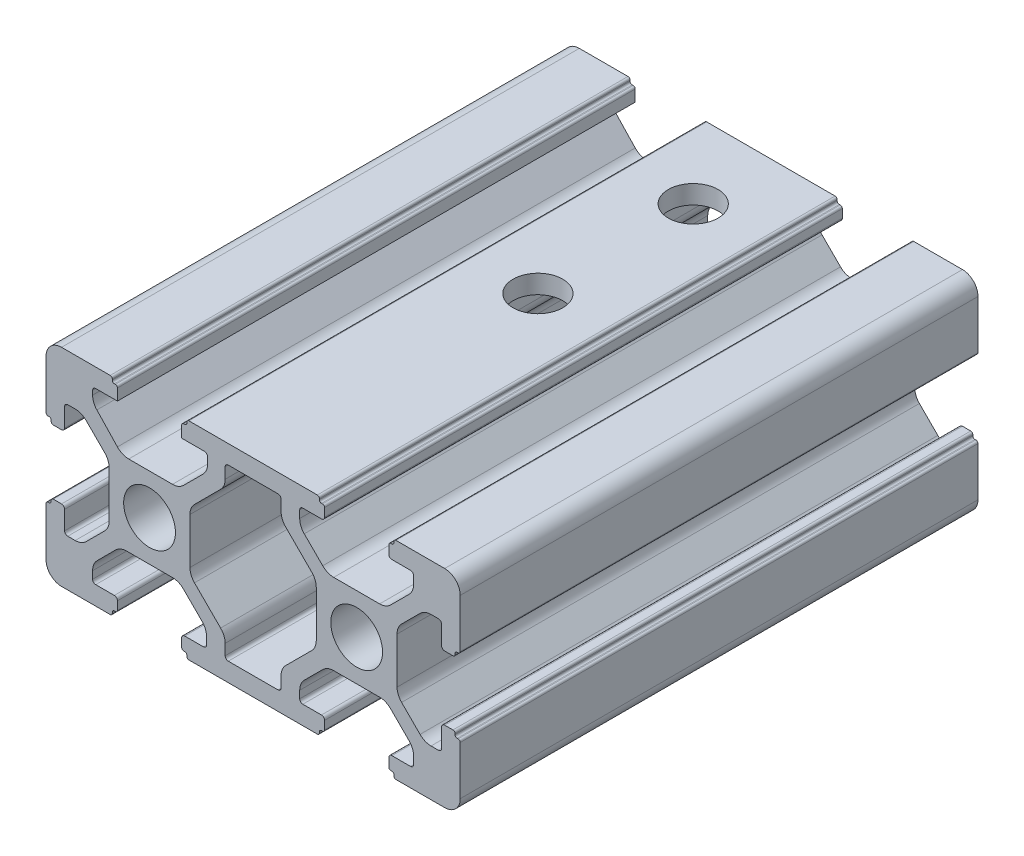
SolidWorks part; units mm, degrees
material "6063-O"
ref_plane "Front Plane" through (0, 0, 0) normal (0, 0, 1) x (1, 0, 0)
ref_plane "Top Plane" through (0, 0, 0) normal (0, 1, 0) x (1, 0, 0)
ref_plane "Right Plane" through (0, 0, 0) normal (1, 0, 0) x (0, 0, -1)
sketch "Sketch1" plane through (0, 0, 0) normal (0, 0, 1) x (1, 0, 0)
  line L0 (1.5, 0) -> (6.2, 0)
  line L1 (40, 1.5) -> (40, 6.2)
  line L2 (38.5, 20) -> (33.8, 20)
  line L3 (0, 18.5) -> (0, 13.8)
  line L4 (17.6, 1.8) -> (22.4, 1.8)
  line L5 (32.218, 13.9) -> (27.782, 13.9)
  line L6 (26.1, 12.218) -> (26.1, 7.782)
  line L7 (17.6, 18.2) -> (22.4, 18.2)
  line L8 (12.218, 13.9) -> (7.9864, 13.9)
  line L9 (6.1, 12.218) -> (6.1, 7.782)
  line L10 (7.782, 6.1) -> (12.218, 6.1)
  line L11 (13.9, 7.782) -> (13.9, 12.218)
  line L12 (27.782, 6.1) -> (32.218, 6.1)
  line L13 (33.9, 7.782) -> (33.9, 12.218)
  line L14 (26.7213, 14.3393) -> (24.9393, 16.1213)
  line L15 (33.2787, 14.3393) -> (35.0607, 16.1213)
  line L16 (34.3393, 13.2787) -> (36.1213, 15.0607)
  line L17 (25.6607, 6.7213) -> (23.1393, 4.2)
  line L18 (15.2, 1.8) -> (13.4, 1.8)
  line L19 (26.7213, 5.6607) -> (24.9393, 3.8787)
  line L20 (24.8, 1.8) -> (26.6, 1.8)
  line L21 (15.3, 18.2) -> (13.1, 18.2)
  line L22 (13.2787, 14.3393) -> (15.1607, 16.2213)
  line L23 (14.3393, 13.2787) -> (16.8607, 15.8)
  line L24 (5.6607, 6.7213) -> (3.8787, 4.9393)
  line L25 (6.7213, 5.6607) -> (4.9393, 3.8787)
  line L26 (6.897, 14.3689) -> (4.9106, 16.4674)
  line L27 (5.6607, 13.2787) -> (3.8787, 15.0607)
  line L28 (14.3393, 6.7213) -> (16.8607, 4.2)
  line L29 (13.2787, 5.6607) -> (15.0607, 3.8787)
  line L30 (24.8, 18.2) -> (26.6, 18.2)
  line L31 (25.6607, 13.2787) -> (23.1393, 15.8)
  line L32 (34.3393, 6.7213) -> (36.1213, 4.9393)
  line L33 (33.2787, 5.6607) -> (35.0607, 3.8787)
  line L34 (1.8, 15.2) -> (1.8, 13.4)
  line L35 (24.5, 2.1) -> (24.5, 2.818)
  line L36 (4.5, 2.1) -> (4.5, 2.818)
  line L37 (2.818, 4.5) -> (2.1, 4.5)
  line L38 (4.5, 17.9) -> (4.5, 17.4986)
  line L39 (2.818, 15.5) -> (2.1, 15.5)
  line L40 (15.6, 17.9) -> (15.6, 17.282)
  line L41 (15.5, 2.818) -> (15.5, 2.1)
  line L42 (38.2, 15.2) -> (38.2, 13.4)
  line L43 (35.5, 2.818) -> (35.5, 2.1)
  line L44 (37.182, 4.5) -> (37.9, 4.5)
  line L45 (35.5, 17.182) -> (35.5, 17.9)
  line L46 (37.182, 15.5) -> (37.9, 15.5)
  line L47 (17.3, 2.1) -> (17.3, 3.1393)
  line L48 (22.7, 2.1) -> (22.7, 3.1393)
  line L49 (17.3, 17.9) -> (17.3, 16.8607)
  line L50 (22.7, 17.9) -> (22.7, 16.8607)
  line L51 (24.5, 17.9) -> (24.5, 17.182)
  line L52 (6.9, 19.3) -> (6.9, 18.2)
  line L53 (13.1, 19.3) -> (13.1, 18.2)
  line L54 (6.9, 1.5) -> (6.9, 0.7)
  line L55 (13.1, 1.5) -> (13.1, 0.7)
  line L56 (13.8, 0) -> (26.2, 0)
  line L57 (6.6, 1.8) -> (4.8, 1.8)
  line L58 (6.9, 18.2) -> (4.8, 18.2)
  line L59 (6.2, 20) -> (1.5, 20)
  line L60 (39.3, 6.9) -> (38.5, 6.9)
  line L61 (39.3, 13.1) -> (38.5, 13.1)
  line L62 (1.5, 13.1) -> (0.7, 13.1)
  line L63 (1.5, 6.9) -> (0.7, 6.9)
  line L64 (0, 6.2) -> (0, 1.5)
  line L65 (1.8, 6.6) -> (1.8, 4.8)
  line L66 (38.2, 6.6) -> (38.2, 4.8)
  line L67 (40, 13.8) -> (40, 18.5)
  line L68 (33.1, 19.3) -> (33.1, 18.5)
  line L69 (26.9, 19.3) -> (26.9, 18.5)
  line L70 (26.9, 1.5) -> (26.9, 0.7)
  line L71 (33.1, 1.5) -> (33.1, 0.7)
  line L72 (33.8, 0) -> (38.5, 0)
  line L73 (33.4, 1.8) -> (35.2, 1.8)
  line L74 (26.2, 20) -> (13.8, 20)
  line L75 (33.4, 18.2) -> (35.2, 18.2)
  line L76 (6.7, 0.5) -> (6.6, 0.5)
  line L77 (6.4, 0.3) -> (6.4, 0.2)
  line L78 (13.3, 0.5) -> (13.4, 0.5)
  line L79 (13.6, 0.3) -> (13.6, 0.2)
  line L80 (26.7, 0.5) -> (26.6, 0.5)
  line L81 (26.4, 0.3) -> (26.4, 0.2)
  line L82 (33.3, 0.5) -> (33.4, 0.5)
  line L83 (33.6, 0.3) -> (33.6, 0.2)
  line L85 (6.4, 19.8) -> (6.4, 19.7)
  line L86 (6.6, 19.5) -> (6.7, 19.5)
  line L87 (13.6, 19.8) -> (13.6, 19.7)
  line L88 (13.4, 19.5) -> (13.3, 19.5)
  line L89 (26.4, 19.8) -> (26.4, 19.7)
  line L90 (26.6, 19.5) -> (26.7, 19.5)
  line L91 (33.6, 19.8) -> (33.6, 19.7)
  line L92 (33.4, 19.5) -> (33.3, 19.5)
  line L93 (0.5, 13.3) -> (0.5, 13.4)
  line L94 (0.3, 13.6) -> (0.2, 13.6)
  line L95 (0.5, 6.7) -> (0.5, 6.6)
  line L96 (0.3, 6.4) -> (0.2, 6.4)
  line L97 (39.5, 13.3) -> (39.5, 13.4)
  line L98 (39.7, 13.6) -> (39.8, 13.6)
  line L99 (39.5, 6.7) -> (39.5, 6.6)
  line L100 (39.7, 6.4) -> (39.8, 6.4)
  circle A0 centre (10, 10) radius 2.5
  circle A1 centre (30, 10) radius 2.5
  arc A2 (38.5, 0) -> (40, 1.5) centre (38.5, 1.5) ccw
  arc A3 (40, 18.5) -> (38.5, 20) centre (38.5, 18.5) ccw
  arc A4 (1.5, 0) -> (0, 1.5) centre (1.5, 1.5) cw
  arc A5 (1.5, 20) -> (0, 18.5) centre (1.5, 18.5) ccw
  arc A6 (26.7213, 5.6607) -> (27.782, 6.1) centre (27.782, 4.6) cw
  arc A7 (32.218, 6.1) -> (33.2787, 5.6607) centre (32.218, 4.6) cw
  arc A8 (33.9, 7.782) -> (34.3393, 6.7213) centre (35.4, 7.782) ccw
  arc A9 (33.2787, 14.3393) -> (32.218, 13.9) centre (32.218, 15.4) cw
  arc A10 (14.3393, 6.7213) -> (13.9, 7.782) centre (15.4, 7.782) cw
  arc A11 (14.3393, 13.2787) -> (13.9, 12.218) centre (15.4, 12.218) ccw
  arc A12 (25.6607, 6.7213) -> (26.1, 7.782) centre (24.6, 7.782) ccw
  arc A13 (26.1, 12.218) -> (25.6607, 13.2787) centre (24.6, 12.218) ccw
  arc A14 (27.782, 13.9) -> (26.7213, 14.3393) centre (27.782, 15.4) cw
  arc A15 (5.6607, 13.2787) -> (6.1, 12.218) centre (4.6, 12.218) cw
  arc A16 (5.6607, 6.7213) -> (6.1, 7.782) centre (4.6, 7.782) ccw
  arc A17 (13.2787, 5.6607) -> (12.218, 6.1) centre (12.218, 4.6) ccw
  arc A18 (6.7213, 5.6607) -> (7.782, 6.1) centre (7.782, 4.6) cw
  arc A19 (13.2787, 14.3393) -> (12.218, 13.9) centre (12.218, 15.4) cw
  arc A20 (6.897, 14.3689) -> (7.9864, 13.9) centre (7.9864, 15.4) ccw
  arc A21 (36.1213, 4.9393) -> (37.182, 4.5) centre (37.182, 6) ccw
  arc A22 (36.1213, 15.0607) -> (37.182, 15.5) centre (37.182, 14) cw
  arc A23 (35.0607, 16.1213) -> (35.5, 17.182) centre (34, 17.182) ccw
  arc A24 (24.5, 17.182) -> (24.9393, 16.1213) centre (26, 17.182) ccw
  arc A25 (22.7, 16.8607) -> (23.1393, 15.8) centre (24.2, 16.8607) ccw
  arc A26 (17.3, 16.8607) -> (16.8607, 15.8) centre (15.8, 16.8607) cw
  arc A27 (4.9106, 16.4674) -> (4.5, 17.4986) centre (6, 17.4986) cw
  arc A28 (15.6, 17.282) -> (15.1607, 16.2213) centre (14.1, 17.282) cw
  arc A29 (3.8787, 15.0607) -> (2.818, 15.5) centre (2.818, 14) ccw
  arc A30 (3.8787, 4.9393) -> (2.818, 4.5) centre (2.818, 6) cw
  arc A31 (4.9393, 3.8787) -> (4.5, 2.818) centre (6, 2.818) ccw
  arc A32 (35.0607, 3.8787) -> (35.5, 2.818) centre (34, 2.818) cw
  arc A33 (24.9393, 3.8787) -> (24.5, 2.818) centre (26, 2.818) ccw
  arc A34 (22.7, 3.1393) -> (23.1393, 4.2) centre (24.2, 3.1393) cw
  arc A35 (17.3, 3.1393) -> (16.8607, 4.2) centre (15.8, 3.1393) ccw
  arc A36 (15.5, 2.818) -> (15.0607, 3.8787) centre (14, 2.818) ccw
  arc A37 (1.8, 6.6) -> (1.5, 6.9) centre (1.5, 6.6) ccw
  arc A38 (1.8, 13.4) -> (1.5, 13.1) centre (1.5, 13.4) cw
  arc A39 (17.6, 18.2) -> (17.3, 17.9) centre (17.6, 17.9) ccw
  arc A40 (22.4, 1.8) -> (22.7, 2.1) centre (22.4, 2.1) ccw
  arc A41 (17.6, 1.8) -> (17.3, 2.1) centre (17.6, 2.1) cw
  arc A42 (15.2, 1.8) -> (15.5, 2.1) centre (15.2, 2.1) ccw
  arc A43 (6.6, 1.8) -> (6.9, 1.5) centre (6.6, 1.5) cw
  arc A44 (13.4, 1.8) -> (13.1, 1.5) centre (13.4, 1.5) ccw
  arc A45 (24.8, 1.8) -> (24.5, 2.1) centre (24.8, 2.1) cw
  arc A46 (35.2, 1.8) -> (35.5, 2.1) centre (35.2, 2.1) ccw
  arc A47 (26.6, 1.8) -> (26.9, 1.5) centre (26.6, 1.5) cw
  arc A48 (33.4, 1.8) -> (33.1, 1.5) centre (33.4, 1.5) ccw
  arc A49 (26.9, 18.5) -> (26.6, 18.2) centre (26.6, 18.5) cw
  arc A50 (33.1, 18.5) -> (33.4, 18.2) centre (33.4, 18.5) ccw
  arc A51 (37.9, 4.5) -> (38.2, 4.8) centre (37.9, 4.8) ccw
  arc A52 (38.5, 13.1) -> (38.2, 13.4) centre (38.5, 13.4) cw
  arc A53 (38.5, 6.9) -> (38.2, 6.6) centre (38.5, 6.6) ccw
  arc A54 (38.2, 15.2) -> (37.9, 15.5) centre (37.9, 15.2) ccw
  arc A55 (35.2, 18.2) -> (35.5, 17.9) centre (35.2, 17.9) cw
  arc A56 (24.8, 18.2) -> (24.5, 17.9) centre (24.8, 17.9) ccw
  arc A57 (22.4, 18.2) -> (22.7, 17.9) centre (22.4, 17.9) cw
  arc A58 (15.3, 18.2) -> (15.6, 17.9) centre (15.3, 17.9) cw
  arc A59 (4.5, 17.9) -> (4.8, 18.2) centre (4.8, 17.9) cw
  arc A60 (1.8, 15.2) -> (2.1, 15.5) centre (2.1, 15.2) cw
  arc A61 (1.8, 4.8) -> (2.1, 4.5) centre (2.1, 4.8) ccw
  arc A62 (4.5, 2.1) -> (4.8, 1.8) centre (4.8, 2.1) ccw
  arc A63 (34.3393, 13.2787) -> (33.9, 12.218) centre (35.4, 12.218) ccw
  arc A64 (6.4, 0.2) -> (6.2, 0) centre (6.2, 0.2) cw
  arc A65 (6.6, 0.5) -> (6.4, 0.3) centre (6.6, 0.3) ccw
  arc A66 (6.7, 0.5) -> (6.9, 0.7) centre (6.7, 0.7) ccw
  arc A67 (13.6, 0.2) -> (13.8, 0) centre (13.8, 0.2) ccw
  arc A68 (13.4, 0.5) -> (13.6, 0.3) centre (13.4, 0.3) cw
  arc A69 (13.3, 0.5) -> (13.1, 0.7) centre (13.3, 0.7) cw
  arc A70 (26.4, 0.2) -> (26.2, 0) centre (26.2, 0.2) cw
  arc A71 (26.6, 0.5) -> (26.4, 0.3) centre (26.6, 0.3) ccw
  arc A72 (26.7, 0.5) -> (26.9, 0.7) centre (26.7, 0.7) ccw
  arc A73 (33.6, 0.2) -> (33.8, 0) centre (33.8, 0.2) ccw
  arc A74 (33.4, 0.5) -> (33.6, 0.3) centre (33.4, 0.3) cw
  arc A75 (33.3, 0.5) -> (33.1, 0.7) centre (33.3, 0.7) cw
  arc A76 (39.8, 6.4) -> (40, 6.2) centre (39.8, 6.2) cw
  arc A77 (39.5, 6.6) -> (39.7, 6.4) centre (39.7, 6.6) ccw
  arc A78 (39.5, 6.7) -> (39.3, 6.9) centre (39.3, 6.7) ccw
  arc A79 (39.5, 13.3) -> (39.3, 13.1) centre (39.3, 13.3) cw
  arc A80 (39.5, 13.4) -> (39.7, 13.6) centre (39.7, 13.4) cw
  arc A81 (39.8, 13.6) -> (40, 13.8) centre (39.8, 13.8) ccw
  arc A82 (33.3, 19.5) -> (33.1, 19.3) centre (33.3, 19.3) ccw
  arc A83 (33.6, 19.7) -> (33.4, 19.5) centre (33.4, 19.7) cw
  arc A84 (33.6, 19.8) -> (33.8, 20) centre (33.8, 19.8) cw
  arc A85 (26.7, 19.5) -> (26.9, 19.3) centre (26.7, 19.3) cw
  arc A86 (26.4, 19.7) -> (26.6, 19.5) centre (26.6, 19.7) ccw
  arc A87 (26.4, 19.8) -> (26.2, 20) centre (26.2, 19.8) ccw
  arc A88 (0.2, 6.4) -> (0, 6.2) centre (0.2, 6.2) ccw
  arc A89 (0.5, 6.6) -> (0.3, 6.4) centre (0.3, 6.6) cw
  arc A90 (0.5, 6.7) -> (0.7, 6.9) centre (0.7, 6.7) cw
  arc A91 (13.3, 19.5) -> (13.1, 19.3) centre (13.3, 19.3) ccw
  arc A92 (13.6, 19.7) -> (13.4, 19.5) centre (13.4, 19.7) cw
  arc A93 (13.6, 19.8) -> (13.8, 20) centre (13.8, 19.8) cw
  arc A94 (6.2, 20) -> (6.4, 19.8) centre (6.2, 19.8) cw
  arc A95 (6.7, 19.5) -> (6.9, 19.3) centre (6.7, 19.3) cw
  arc A96 (6.4, 19.7) -> (6.6, 19.5) centre (6.6, 19.7) ccw
  arc A97 (0.5, 13.3) -> (0.7, 13.1) centre (0.7, 13.3) ccw
  arc A98 (0.2, 13.6) -> (0, 13.8) centre (0.2, 13.8) cw
  arc A99 (0.5, 13.4) -> (0.3, 13.6) centre (0.3, 13.4) ccw
  point P87 (0, 0)
  point P178 (1.8, 6.9)
  point P181 (1.8, 13.1)
  point P186 (22.7, 1.8)
  point P193 (6.9, 1.8)
  point P204 (33.1, 1.8)
  point P209 (33.1, 18.2)
  point P216 (38.2, 6.9)
  point P243 (6.9, 0.5)
  point P248 (13.6, 0.5)
  point P257 (26.9, 0.5)
extrude "Boss-Extrude2" add sketch "Sketch1" along normal blind 50 contours A57 L7 A39 L49 A26 L23 A11 L11 A10 L28 A35 L47 A41 L4 A40 L48 A34 L17 A12 L6 A13 L31 A25 L50 | A0 | A1 | L59 A5 L3 A98 L94 A99 L93 A97 L62 A38 L34 A60 L39 A29 L27 A15 L9 A16 L24 A30 L37 A61 L65 A37 L63 A90 L95 A89 L96 A88 L64 A4 L0 A64 L77 A65 L76 A66 L54 A43 L57 A62 L36 A31 L25 A18 L10 A17 L29 A36 L41 A42 L18 A44 L55 A69 L78 A68 L79 A67 L56 A70 L81 A71 L80 A72 L70 A47 L20 A45 L35 A33 L19 A6 L12 A7 L33 A32 L43 A46 L73 A48 L71 A75 L82 A74 L83 A73 L72 A2 L1 A76 L100 A77 L99 A78 L60 A53 L66 A51 L44 A21 L32 A8 L13 A63 L16 A22 L46 A54 L42 A52 L61 A79 L97 A80 L98 A81 L67 A3 L2 A84 L91 A83 L92 A82 L68 A50 L75 A55 L45 A23 L15 A9 L5 A14 L14 A24 L51 A56 L30 A49 L69 A85 L90 A86 L89 A87 L74 A93 L87 A92 L88 A91 L53 L21 A58 L40 A28 L22 A19 L8 A20 L26 A27 L38 A59 L58 L52 A95 L86 A96 L85 A94
sketch "Sketch2" plane through (0, 20, 0) normal (0, 1, 0) x (1, 0, 0)
  line L0 (26.2, 0) -> (13.8, 0) construction
  line L3 (26.2, -50) -> (13.8, -50) construction
  circle A0 centre (20, -7.5) radius 2.4
  circle A1 centre (20, -22.5) radius 2.4
  point P4 (0, 0)
  point P9 (20, 0)
  dimension "D1" = 4.8
  dimension "D2" = 15
  dimension "D3" = 27.5
extrude "Cut-Extrude1" cut sketch "Sketch2" against normal blind 39
